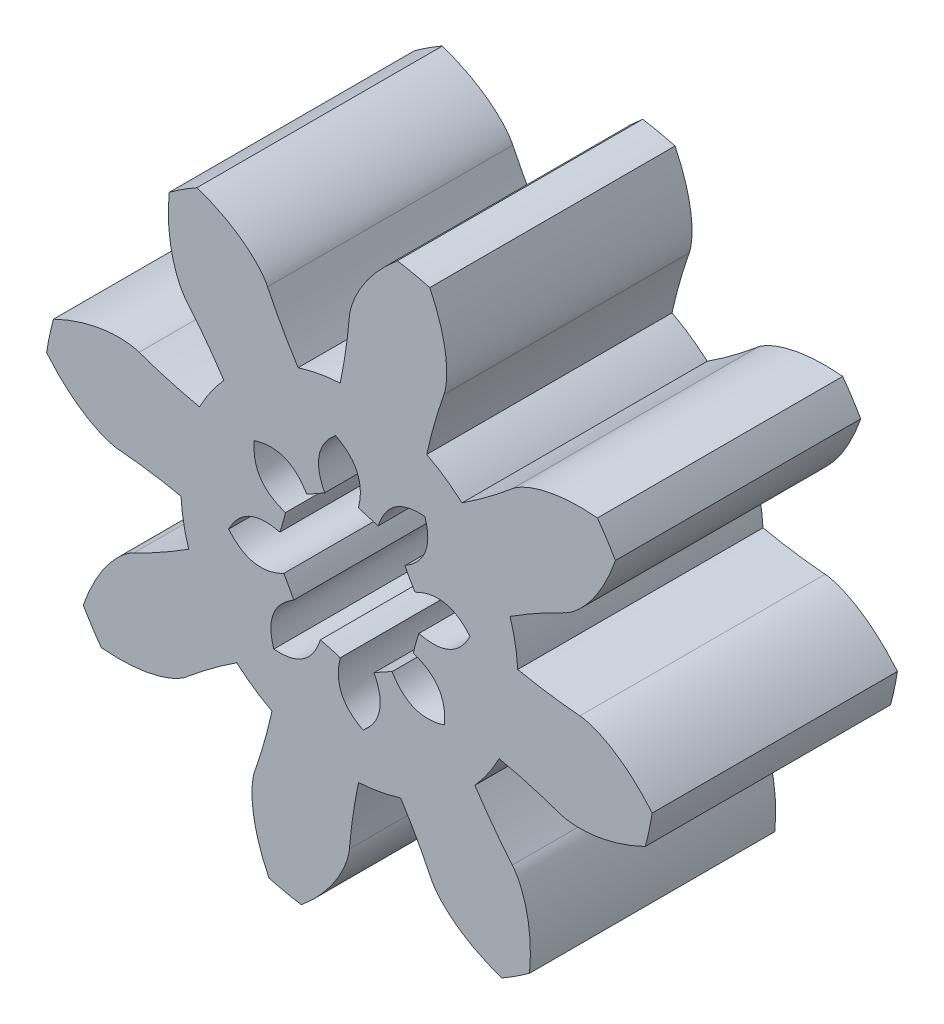
SolidWorks part; units mm, degrees
ref_plane "前视基准面" through (0, 0, 0) normal (0, 0, 1) x (1, 0, 0)
ref_plane "上视基准面" through (0, 0, 0) normal (0, 1, 0) x (1, 0, 0)
ref_plane "右视基准面" through (0, 0, 0) normal (1, 0, 0) x (0, 0, -1)
sketch "草图2" plane through (0, 0, 0) normal (0, 0, 1) x (1, 0, 0)
  line L0 (1021.8666, 5609.6844) -> (5289.866, 5609.6844) construction
  line L1 (0, 0) -> (-0.3395, 2.9526) construction
  line L2 (0, 0) -> (0.0894, 5.9993) construction
  line L3 (0, 0) -> (1.9737, 9.2034) construction
  line L4 (0, 0) -> (6.3967, 9.2712) construction
  circle A0 centre (0, 0) radius 1 construction
  circle A1 centre (0, 0) radius 4.125
  circle A2 centre (0, 0) radius 7.5
  circle A3 centre (0, 0) radius 6
  spline S0 degree 2 poles (-0.6033, 1.6046) (-1.0063, 2.3892) (-0.3395, 2.9526) knots 0 0 0 1 1 1
  spline S1 degree 2 poles (0.2233, 1.6996) (0.4378, 2.5552) (-0.3395, 2.9526) knots 0 0 0 1 1 1
  spline S2 degree 2 poles (0.708, 1.5612) (0.9778, 2.401) (1.8478, 2.3279) knots 0 0 0 1 1 1
  spline S3 degree 2 poles (1.3597, 1.0439) (2.1164, 1.4973) (1.8478, 2.3279) knots 0 0 0 1 1 1
  spline S4 degree 2 poles (1.6046, 0.6033) (2.3892, 1.0063) (2.9526, 0.3395) knots 0 0 0 1 1 1
  spline S5 degree 2 poles (1.6996, -0.2233) (2.5552, -0.4378) (2.9526, 0.3395) knots 0 0 0 1 1 1
  spline S6 degree 2 poles (1.5612, -0.708) (2.401, -0.9778) (2.3279, -1.8478) knots 0 0 0 1 1 1
  spline S7 degree 2 poles (1.0439, -1.3597) (1.4973, -2.1164) (2.3279, -1.8478) knots 0 0 0 1 1 1
  spline S8 degree 2 poles (0.6033, -1.6046) (1.0063, -2.3892) (0.3395, -2.9526) knots 0 0 0 1 1 1
  spline S9 degree 2 poles (-0.2233, -1.6996) (-0.4378, -2.5552) (0.3395, -2.9526) knots 0 0 0 1 1 1
  spline S10 degree 2 poles (-0.708, -1.5612) (-0.9778, -2.401) (-1.8478, -2.3279) knots 0 0 0 1 1 1
  spline S11 degree 2 poles (-1.3597, -1.0439) (-2.1164, -1.4973) (-1.8478, -2.3279) knots 0 0 0 1 1 1
  spline S12 degree 2 poles (-1.6046, -0.6033) (-2.3892, -1.0063) (-2.9526, -0.3395) knots 0 0 0 1 1 1
  spline S13 degree 2 poles (-1.6996, 0.2233) (-2.5552, 0.4378) (-2.9526, -0.3395) knots 0 0 0 1 1 1
  spline S14 degree 2 poles (-1.5612, 0.708) (-2.401, 0.9778) (-2.3279, 1.8478) knots 0 0 0 1 1 1
  spline S15 degree 2 poles (-1.0439, 1.3597) (-1.4973, 2.1164) (-2.3279, 1.8478) knots 0 0 0 1 1 1
  spline S16 degree 2 poles (-1.0439, 1.3597) (-0.8193, 1.4745) (-0.6033, 1.6046) knots 0 0 0 1 1 1
  spline S17 degree 2 poles (0.2233, 1.6996) (0.4633, 1.622) (0.708, 1.5612) knots 0 0 0 1 1 1
  spline S18 degree 2 poles (1.3597, 1.0439) (1.4745, 0.8193) (1.6046, 0.6033) knots 0 0 0 1 1 1
  spline S19 degree 2 poles (1.6996, -0.2233) (1.622, -0.4633) (1.5612, -0.708) knots 0 0 0 1 1 1
  spline S20 degree 2 poles (1.0439, -1.3597) (0.8193, -1.4745) (0.6033, -1.6046) knots 0 0 0 1 1 1
  spline S21 degree 2 poles (-0.2233, -1.6996) (-0.4633, -1.622) (-0.708, -1.5612) knots 0 0 0 1 1 1
  spline S22 degree 2 poles (-1.3597, -1.0439) (-1.4745, -0.8193) (-1.6046, -0.6033) knots 0 0 0 1 1 1
  spline S23 degree 2 poles (-1.6996, 0.2233) (-1.622, 0.4633) (-1.5612, 0.708) knots 0 0 0 1 1 1
  spline S24 degree 4 poles (0, 5.6382) (0.0001, 5.6427) (0.0007, 5.6555) (0.0031, 5.6797) (0.0087, 5.7189) (0.0184, 5.7686) (0.0339, 5.8322) (0.0558, 5.9064) (0.0838, 5.9869) (0.1183, 6.0733) (0.1564, 6.1582) (0.1977, 6.2417) (0.2417, 6.3236) (0.2985, 6.4213) (0.3712, 6.5363) (0.463, 6.6672) (0.5748, 6.8112) (0.6967, 6.9529) (0.8232, 7.0879) (0.9581, 7.219) (1.0936, 7.3421) (1.2411, 7.4639) (1.3809, 7.5734) (1.5445, 7.6892) (1.6787, 7.7806) (1.8629, 7.8935) (1.9738, 7.9579) (2.1059, 8.0304) (2.1658, 8.0612) (2.2027, 8.0802) knots 0 0 0 0 0 0.005377 0.015084 0.028532 0.04661 0.064855 0.092111 0.119476 0.146842 0.174209 0.201575 0.228941 0.256307 0.307035 0.361767 0.4165 0.471232 0.525964 0.580697 0.635429 0.690161 0.744894 0.799626 0.854358 0.909091 0.954545 1 1 1 1 1 construction
  spline S25 degree 4 poles (0, 5.6382) (0.0001, 5.6427) (0.0007, 5.6555) (0.0031, 5.6797) (0.0087, 5.7189) (0.0184, 5.7686) (0.0339, 5.8322) (0.0558, 5.9064) (0.0838, 5.9869) (0.1183, 6.0733) (0.1564, 6.1582) (0.1977, 6.2417) (0.2417, 6.3236) (0.2985, 6.4213) (0.3712, 6.5363) (0.463, 6.6672) (0.5748, 6.8112) (0.6967, 6.9529) (0.8232, 7.0879) (0.9581, 7.219) (1.0611, 7.3126) (1.1345, 7.3751) (1.1722, 7.4063) (1.1737, 7.4076) knots 0 0 0 0 0 0.005377 0.015084 0.028532 0.04661 0.064855 0.092111 0.119476 0.146842 0.174209 0.201575 0.228941 0.256307 0.307035 0.361767 0.4165 0.471232 0.525964 0.580697 0.635429 0.637784 0.637784 0.637784 0.637784 0.637784
  spline S26 degree 2 poles (0, 5.6382) (-0.0656, 4.8718) (-0.2233, 4.119) knots 0 0 0 1 1 1
  spline S27 degree 2 poles (2.3119, 5.1424) (2.0575, 4.4165) (1.8926, 3.6652) knots 0 0 0 1 1 1
  spline S28 degree 4 poles (2.3119, 5.1424) (2.3137, 5.1466) (2.3184, 5.1585) (2.3262, 5.1815) (2.3371, 5.2196) (2.3486, 5.2689) (2.3606, 5.3332) (2.371, 5.4099) (2.3785, 5.4948) (2.3824, 5.5877) (2.3825, 5.6808) (2.3791, 5.7738) (2.3725, 5.8667) (2.3608, 5.9791) (2.3416, 6.1138) (2.3116, 6.2707) (2.2687, 6.4479) (2.2155, 6.6271) (2.1556, 6.8022) (2.0863, 6.9771) (2.0307, 7.1047) (1.9894, 7.1917) (1.9678, 7.2357) (1.967, 7.2375) knots 0 0 0 0 0 0.005377 0.015084 0.028532 0.04661 0.064855 0.092111 0.119476 0.146842 0.174209 0.201575 0.228941 0.256307 0.307035 0.361767 0.4165 0.471232 0.525964 0.580697 0.635429 0.637784 0.637784 0.637784 0.637784 0.637784
  spline S29 degree 2 poles (3.9868, 3.9868) (3.3985, 3.4913) (2.7547, 3.0704) knots 0 0 0 1 1 1
  spline S30 degree 4 poles (3.9868, 3.9868) (3.9901, 3.9899) (3.9996, 3.9986) (4.0183, 4.014) (4.05, 4.0378) (4.092, 4.066) (4.148, 4.1001) (4.2159, 4.137) (4.2926, 4.1741) (4.3781, 4.2108) (4.4651, 4.2439) (4.5533, 4.2738) (4.6424, 4.3006) (4.7516, 4.3295) (4.8844, 4.3594) (5.0418, 4.387) (5.2227, 4.4098) (5.4091, 4.4237) (5.594, 4.4298) (5.7821, 4.4272) (5.9211, 4.4205) (6.0172, 4.4127) (6.0659, 4.4082) (6.0679, 4.408) knots 0 0 0 0 0 0.005377 0.015084 0.028532 0.04661 0.064855 0.092111 0.119476 0.146842 0.174209 0.201575 0.228941 0.256307 0.307035 0.361767 0.4165 0.471232 0.525964 0.580697 0.635429 0.637784 0.637784 0.637784 0.637784 0.637784
  point P48 (0, 0)
  point P70 (0, 0)
  dimension "D1" = 2
  dimension "D2" = 15
  dimension "D3" = 8.25
  dimension "D4" = 12
  dimension "D5" = 11.25
  dimension "D6" = 33.75
sketch "草图3" plane through (0, 0, 0) normal (0, 0, 1) x (1, 0, 0)
  circle A0 centre (0, 0) radius 7.5 construction
  circle A1 centre (0, 0) radius 4.125 construction
  arc A3 (2.3119, 5.1424) -> (1.8926, 3.6652) centre (14.2794, 0.9473) ccw construction
  arc A4 (-0.2233, 4.119) -> (0, 5.6382) centre (-12.6353, 6.7192) ccw construction
  arc A5 (1.967, 7.2375) -> (1.1737, 7.4076) centre (0, 0) ccw
  arc A6 (2.7547, 3.0704) -> (1.8926, 3.6652) centre (0, 0) ccw
  arc A8 (2.3119, 5.1424) -> (1.8926, 3.6652) centre (14.2794, 0.9473) ccw
  arc A9 (-0.2233, 4.119) -> (0, 5.6382) centre (-12.6353, 6.7192) ccw
  arc A10 (2.7547, 3.0704) -> (3.9868, 3.9868) centre (-4.1833, 13.6857) ccw
  arc A11 (6.5085, 3.7268) -> (6.0679, 4.408) centre (0, 0) ccw
  arc A12 (5.271, 2.0014) -> (3.93, 1.2534) centre (10.7669, -9.4272) ccw
  arc A13 (4.119, 0.2233) -> (3.93, 1.2534) centre (0, 0) ccw
  arc A14 (4.119, 0.2233) -> (5.6382, 0) centre (6.7192, 12.6353) ccw
  arc A15 (7.2375, -1.967) -> (7.4076, -1.1737) centre (0, 0) ccw
  arc A16 (5.1424, -2.3119) -> (3.6652, -1.8926) centre (0.9473, -14.2794) ccw
  arc A17 (3.0704, -2.7547) -> (3.6652, -1.8926) centre (0, 0) ccw
  arc A18 (3.0704, -2.7547) -> (3.9868, -3.9868) centre (13.6857, 4.1833) ccw
  arc A19 (3.7268, -6.5085) -> (4.408, -6.0679) centre (0, 0) ccw
  arc A20 (2.0014, -5.271) -> (1.2534, -3.93) centre (-9.4272, -10.7669) ccw
  arc A21 (0.2233, -4.119) -> (1.2534, -3.93) centre (0, 0) ccw
  arc A22 (0.2233, -4.119) -> (0, -5.6382) centre (12.6353, -6.7192) ccw
  arc A23 (-1.967, -7.2375) -> (-1.1737, -7.4076) centre (0, 0) ccw
  arc A24 (-2.3119, -5.1424) -> (-1.8926, -3.6652) centre (-14.2794, -0.9473) ccw
  arc A25 (-2.7547, -3.0704) -> (-1.8926, -3.6652) centre (0, 0) ccw
  arc A26 (-2.7547, -3.0704) -> (-3.9868, -3.9868) centre (4.1833, -13.6857) ccw
  arc A27 (-6.5085, -3.7268) -> (-6.0679, -4.408) centre (0, 0) ccw
  arc A28 (-5.271, -2.0014) -> (-3.93, -1.2534) centre (-10.7669, 9.4272) ccw
  arc A29 (-4.119, -0.2233) -> (-3.93, -1.2534) centre (0, 0) ccw
  arc A30 (-4.119, -0.2233) -> (-5.6382, 0) centre (-6.7192, -12.6353) ccw
  arc A31 (-7.2375, 1.967) -> (-7.4076, 1.1737) centre (0, 0) ccw
  arc A32 (-5.1424, 2.3119) -> (-3.6652, 1.8926) centre (-0.9473, 14.2794) ccw
  arc A33 (-3.0704, 2.7547) -> (-3.6652, 1.8926) centre (0, 0) ccw
  arc A34 (-3.0704, 2.7547) -> (-3.9868, 3.9868) centre (-13.6857, -4.1833) ccw
  arc A35 (-3.7268, 6.5085) -> (-4.408, 6.0679) centre (0, 0) ccw
  arc A36 (-2.0014, 5.271) -> (-1.2534, 3.93) centre (9.4272, 10.7669) ccw
  arc A37 (-0.2233, 4.119) -> (-1.2534, 3.93) centre (0, 0) ccw
  spline S1 degree 4 poles (-1827.5886, 812.2338) (-20.5673, 13.6102) (1.554, 4.3385) (2.187, 4.6983) (2.3371, 5.2196) (2.3486, 5.2689) (2.3606, 5.3332) (2.371, 5.4099) (2.3785, 5.4948) (2.3824, 5.5877) (2.3825, 5.6808) (2.3791, 5.7738) (2.3725, 5.8667) (2.3608, 5.9791) (2.3416, 6.1138) (2.3116, 6.2707) (2.2687, 6.4479) (2.2155, 6.6271) (2.1556, 6.8022) (2.0863, 6.9771) (1.4771, 8.3746) (-0.1138, 10.0692) (14.7711, -11.5034) (-1169.1431, 1628.4646) knots -0.591364 -0.591364 -0.591364 -0.591364 -0.591364 0.005377 0.015084 0.028532 0.04661 0.064855 0.092111 0.119476 0.146842 0.174209 0.201575 0.228941 0.256307 0.307035 0.361767 0.4165 0.471232 0.525964 0.580697 0.635429 2.294974 2.294974 2.294974 2.294974 2.294974 only from (2.3119, 5.1424) to (1.967, 7.2375) construction
  spline S2 degree 4 poles (1999.9325, -8.5916) (24.3395, 3.9798) (0.3616, 4.5942) (-0.0681, 5.1819) (0.0087, 5.7189) (0.0184, 5.7686) (0.0339, 5.8322) (0.0558, 5.9064) (0.0838, 5.9869) (0.1183, 6.0733) (0.1564, 6.1582) (0.1977, 6.2417) (0.2417, 6.3236) (0.2985, 6.4213) (0.3712, 6.5363) (0.463, 6.6672) (0.5748, 6.8112) (0.6967, 6.9529) (0.8232, 7.0879) (0.9581, 7.219) (2.0868, 8.2439) (4.2327, 9.1371) (-18.1891, -4.435) (1734.0829, 1005.8577) knots -0.591364 -0.591364 -0.591364 -0.591364 -0.591364 0.005377 0.015084 0.028532 0.04661 0.064855 0.092111 0.119476 0.146842 0.174209 0.201575 0.228941 0.256307 0.307035 0.361767 0.4165 0.471232 0.525964 0.580697 0.635429 2.294974 2.294974 2.294974 2.294974 2.294974 only from (0, 5.6382) to (1.1737, 7.4076) construction
  spline S3 degree 4 poles (3.9868, 3.9868) (3.9901, 3.9899) (3.9996, 3.9986) (4.0183, 4.014) (4.05, 4.0378) (4.092, 4.066) (4.148, 4.1001) (4.2159, 4.137) (4.2926, 4.1741) (4.3781, 4.2108) (4.4651, 4.2439) (4.5533, 4.2738) (4.6424, 4.3006) (4.7516, 4.3295) (4.8844, 4.3594) (5.0418, 4.387) (5.2227, 4.4098) (5.4091, 4.4237) (5.594, 4.4298) (5.7821, 4.4272) (5.9211, 4.4205) (6.0172, 4.4127) (6.0659, 4.4082) (6.0679, 4.408) knots 0 0 0 0 0 0.005377 0.015084 0.028532 0.04661 0.064855 0.092111 0.119476 0.146842 0.174209 0.201575 0.228941 0.256307 0.307035 0.361767 0.4165 0.471232 0.525964 0.580697 0.635429 0.637784 0.637784 0.637784 0.637784 0.637784
  spline S4 degree 4 poles (2.3119, 5.1424) (2.3137, 5.1466) (2.3184, 5.1585) (2.3262, 5.1815) (2.3371, 5.2196) (2.3486, 5.2689) (2.3606, 5.3332) (2.371, 5.4099) (2.3785, 5.4948) (2.3824, 5.5877) (2.3825, 5.6808) (2.3791, 5.7738) (2.3725, 5.8667) (2.3608, 5.9791) (2.3416, 6.1138) (2.3116, 6.2707) (2.2687, 6.4479) (2.2155, 6.6271) (2.1556, 6.8022) (2.0863, 6.9771) (2.0307, 7.1047) (1.9894, 7.1917) (1.9678, 7.2357) (1.967, 7.2375) knots 0 0 0 0 0 0.005377 0.015084 0.028532 0.04661 0.064855 0.092111 0.119476 0.146842 0.174209 0.201575 0.228941 0.256307 0.307035 0.361767 0.4165 0.471232 0.525964 0.580697 0.635429 0.637784 0.637784 0.637784 0.637784 0.637784
  spline S5 degree 4 poles (0, 5.6382) (0.0001, 5.6427) (0.0007, 5.6555) (0.0031, 5.6797) (0.0087, 5.7189) (0.0184, 5.7686) (0.0339, 5.8322) (0.0558, 5.9064) (0.0838, 5.9869) (0.1183, 6.0733) (0.1564, 6.1582) (0.1977, 6.2417) (0.2417, 6.3236) (0.2985, 6.4213) (0.3712, 6.5363) (0.463, 6.6672) (0.5748, 6.8112) (0.6967, 6.9529) (0.8232, 7.0879) (0.9581, 7.219) (1.0611, 7.3126) (1.1345, 7.3751) (1.1722, 7.4063) (1.1737, 7.4076) knots 0 0 0 0 0 0.005377 0.015084 0.028532 0.04661 0.064855 0.092111 0.119476 0.146842 0.174209 0.201575 0.228941 0.256307 0.307035 0.361767 0.4165 0.471232 0.525964 0.580697 0.635429 0.637784 0.637784 0.637784 0.637784 0.637784
  spline S6 degree 4 poles (5.271, 2.0014) (5.2752, 2.0031) (5.287, 2.0082) (5.3087, 2.019) (5.3434, 2.0382) (5.3864, 2.0649) (5.4404, 2.102) (5.5019, 2.1488) (5.5673, 2.2036) (5.6357, 2.2665) (5.7016, 2.3322) (5.765, 2.4004) (5.826, 2.4707) (5.8972, 2.5585) (5.9789, 2.6673) (6.0686, 2.7995) (6.1636, 2.9552) (6.2527, 3.1195) (6.3341, 3.2856) (6.4088, 3.4583) (6.4597, 3.5879) (6.492, 3.6786) (6.5079, 3.7249) (6.5085, 3.7268) knots 0 0 0 0 0 0.005377 0.015084 0.028532 0.04661 0.064855 0.092111 0.119476 0.146842 0.174209 0.201575 0.228941 0.256307 0.307035 0.361767 0.4165 0.471232 0.525964 0.580697 0.635429 0.637784 0.637784 0.637784 0.637784 0.637784
  spline S7 degree 4 poles (5.6382, 0) (5.6427, -0.0001) (5.6555, -0.0007) (5.6797, -0.0031) (5.7189, -0.0087) (5.7686, -0.0184) (5.8322, -0.0339) (5.9064, -0.0558) (5.9869, -0.0838) (6.0733, -0.1183) (6.1582, -0.1564) (6.2417, -0.1977) (6.3236, -0.2417) (6.4213, -0.2985) (6.5363, -0.3712) (6.6672, -0.463) (6.8112, -0.5748) (6.9529, -0.6967) (7.0879, -0.8232) (7.219, -0.9581) (7.3126, -1.0611) (7.3751, -1.1345) (7.4063, -1.1722) (7.4076, -1.1737) knots 0 0 0 0 0 0.005377 0.015084 0.028532 0.04661 0.064855 0.092111 0.119476 0.146842 0.174209 0.201575 0.228941 0.256307 0.307035 0.361767 0.4165 0.471232 0.525964 0.580697 0.635429 0.637784 0.637784 0.637784 0.637784 0.637784
  spline S8 degree 4 poles (5.1424, -2.3119) (5.1466, -2.3137) (5.1585, -2.3184) (5.1815, -2.3262) (5.2196, -2.3371) (5.2689, -2.3486) (5.3332, -2.3606) (5.4099, -2.371) (5.4948, -2.3785) (5.5877, -2.3824) (5.6808, -2.3825) (5.7738, -2.3791) (5.8667, -2.3725) (5.9791, -2.3608) (6.1138, -2.3416) (6.2707, -2.3116) (6.4479, -2.2687) (6.6271, -2.2155) (6.8022, -2.1556) (6.9771, -2.0863) (7.1047, -2.0307) (7.1917, -1.9894) (7.2357, -1.9678) (7.2375, -1.967) knots 0 0 0 0 0 0.005377 0.015084 0.028532 0.04661 0.064855 0.092111 0.119476 0.146842 0.174209 0.201575 0.228941 0.256307 0.307035 0.361767 0.4165 0.471232 0.525964 0.580697 0.635429 0.637784 0.637784 0.637784 0.637784 0.637784
  spline S9 degree 4 poles (3.9868, -3.9868) (3.9899, -3.9901) (3.9986, -3.9996) (4.014, -4.0183) (4.0378, -4.05) (4.066, -4.092) (4.1001, -4.148) (4.137, -4.2159) (4.1741, -4.2926) (4.2108, -4.3781) (4.2439, -4.4651) (4.2738, -4.5533) (4.3006, -4.6424) (4.3295, -4.7516) (4.3594, -4.8844) (4.387, -5.0418) (4.4098, -5.2227) (4.4237, -5.4091) (4.4298, -5.594) (4.4272, -5.7821) (4.4205, -5.9211) (4.4127, -6.0172) (4.4082, -6.0659) (4.408, -6.0679) knots 0 0 0 0 0 0.005377 0.015084 0.028532 0.04661 0.064855 0.092111 0.119476 0.146842 0.174209 0.201575 0.228941 0.256307 0.307035 0.361767 0.4165 0.471232 0.525964 0.580697 0.635429 0.637784 0.637784 0.637784 0.637784 0.637784
  spline S10 degree 4 poles (2.0014, -5.271) (2.0031, -5.2752) (2.0082, -5.287) (2.019, -5.3087) (2.0382, -5.3434) (2.0649, -5.3864) (2.102, -5.4404) (2.1488, -5.5019) (2.2036, -5.5673) (2.2665, -5.6357) (2.3322, -5.7016) (2.4004, -5.765) (2.4707, -5.826) (2.5585, -5.8972) (2.6673, -5.9789) (2.7995, -6.0686) (2.9552, -6.1636) (3.1195, -6.2527) (3.2856, -6.3341) (3.4583, -6.4088) (3.5879, -6.4597) (3.6786, -6.492) (3.7249, -6.5079) (3.7268, -6.5085) knots 0 0 0 0 0 0.005377 0.015084 0.028532 0.04661 0.064855 0.092111 0.119476 0.146842 0.174209 0.201575 0.228941 0.256307 0.307035 0.361767 0.4165 0.471232 0.525964 0.580697 0.635429 0.637784 0.637784 0.637784 0.637784 0.637784
  spline S11 degree 4 poles (0, -5.6382) (-0.0001, -5.6427) (-0.0007, -5.6555) (-0.0031, -5.6797) (-0.0087, -5.7189) (-0.0184, -5.7686) (-0.0339, -5.8322) (-0.0558, -5.9064) (-0.0838, -5.9869) (-0.1183, -6.0733) (-0.1564, -6.1582) (-0.1977, -6.2417) (-0.2417, -6.3236) (-0.2985, -6.4213) (-0.3712, -6.5363) (-0.463, -6.6672) (-0.5748, -6.8112) (-0.6967, -6.9529) (-0.8232, -7.0879) (-0.9581, -7.219) (-1.0611, -7.3126) (-1.1345, -7.3751) (-1.1722, -7.4063) (-1.1737, -7.4076) knots 0 0 0 0 0 0.005377 0.015084 0.028532 0.04661 0.064855 0.092111 0.119476 0.146842 0.174209 0.201575 0.228941 0.256307 0.307035 0.361767 0.4165 0.471232 0.525964 0.580697 0.635429 0.637784 0.637784 0.637784 0.637784 0.637784
  spline S12 degree 4 poles (-2.3119, -5.1424) (-2.3137, -5.1466) (-2.3184, -5.1585) (-2.3262, -5.1815) (-2.3371, -5.2196) (-2.3486, -5.2689) (-2.3606, -5.3332) (-2.371, -5.4099) (-2.3785, -5.4948) (-2.3824, -5.5877) (-2.3825, -5.6808) (-2.3791, -5.7738) (-2.3725, -5.8667) (-2.3608, -5.9791) (-2.3416, -6.1138) (-2.3116, -6.2707) (-2.2687, -6.4479) (-2.2155, -6.6271) (-2.1556, -6.8022) (-2.0863, -6.9771) (-2.0307, -7.1047) (-1.9894, -7.1917) (-1.9678, -7.2357) (-1.967, -7.2375) knots 0 0 0 0 0 0.005377 0.015084 0.028532 0.04661 0.064855 0.092111 0.119476 0.146842 0.174209 0.201575 0.228941 0.256307 0.307035 0.361767 0.4165 0.471232 0.525964 0.580697 0.635429 0.637784 0.637784 0.637784 0.637784 0.637784
  spline S13 degree 4 poles (-3.9868, -3.9868) (-3.9901, -3.9899) (-3.9996, -3.9986) (-4.0183, -4.014) (-4.05, -4.0378) (-4.092, -4.066) (-4.148, -4.1001) (-4.2159, -4.137) (-4.2926, -4.1741) (-4.3781, -4.2108) (-4.4651, -4.2439) (-4.5533, -4.2738) (-4.6424, -4.3006) (-4.7516, -4.3295) (-4.8844, -4.3594) (-5.0418, -4.387) (-5.2227, -4.4098) (-5.4091, -4.4237) (-5.594, -4.4298) (-5.7821, -4.4272) (-5.9211, -4.4205) (-6.0172, -4.4127) (-6.0659, -4.4082) (-6.0679, -4.408) knots 0 0 0 0 0 0.005377 0.015084 0.028532 0.04661 0.064855 0.092111 0.119476 0.146842 0.174209 0.201575 0.228941 0.256307 0.307035 0.361767 0.4165 0.471232 0.525964 0.580697 0.635429 0.637784 0.637784 0.637784 0.637784 0.637784
  spline S14 degree 4 poles (-5.271, -2.0014) (-5.2752, -2.0031) (-5.287, -2.0082) (-5.3087, -2.019) (-5.3434, -2.0382) (-5.3864, -2.0649) (-5.4404, -2.102) (-5.5019, -2.1488) (-5.5673, -2.2036) (-5.6357, -2.2665) (-5.7016, -2.3322) (-5.765, -2.4004) (-5.826, -2.4707) (-5.8972, -2.5585) (-5.9789, -2.6673) (-6.0686, -2.7995) (-6.1636, -2.9552) (-6.2527, -3.1195) (-6.3341, -3.2856) (-6.4088, -3.4583) (-6.4597, -3.5879) (-6.492, -3.6786) (-6.5079, -3.7249) (-6.5085, -3.7268) knots 0 0 0 0 0 0.005377 0.015084 0.028532 0.04661 0.064855 0.092111 0.119476 0.146842 0.174209 0.201575 0.228941 0.256307 0.307035 0.361767 0.4165 0.471232 0.525964 0.580697 0.635429 0.637784 0.637784 0.637784 0.637784 0.637784
  spline S15 degree 4 poles (-5.6382, 0) (-5.6427, 0.0001) (-5.6555, 0.0007) (-5.6797, 0.0031) (-5.7189, 0.0087) (-5.7686, 0.0184) (-5.8322, 0.0339) (-5.9064, 0.0558) (-5.9869, 0.0838) (-6.0733, 0.1183) (-6.1582, 0.1564) (-6.2417, 0.1977) (-6.3236, 0.2417) (-6.4213, 0.2985) (-6.5363, 0.3712) (-6.6672, 0.463) (-6.8112, 0.5748) (-6.9529, 0.6967) (-7.0879, 0.8232) (-7.219, 0.9581) (-7.3126, 1.0611) (-7.3751, 1.1345) (-7.4063, 1.1722) (-7.4076, 1.1737) knots 0 0 0 0 0 0.005377 0.015084 0.028532 0.04661 0.064855 0.092111 0.119476 0.146842 0.174209 0.201575 0.228941 0.256307 0.307035 0.361767 0.4165 0.471232 0.525964 0.580697 0.635429 0.637784 0.637784 0.637784 0.637784 0.637784
  spline S16 degree 4 poles (-5.1424, 2.3119) (-5.1466, 2.3137) (-5.1585, 2.3184) (-5.1815, 2.3262) (-5.2196, 2.3371) (-5.2689, 2.3486) (-5.3332, 2.3606) (-5.4099, 2.371) (-5.4948, 2.3785) (-5.5877, 2.3824) (-5.6808, 2.3825) (-5.7738, 2.3791) (-5.8667, 2.3725) (-5.9791, 2.3608) (-6.1138, 2.3416) (-6.2707, 2.3116) (-6.4479, 2.2687) (-6.6271, 2.2155) (-6.8022, 2.1556) (-6.9771, 2.0863) (-7.1047, 2.0307) (-7.1917, 1.9894) (-7.2357, 1.9678) (-7.2375, 1.967) knots 0 0 0 0 0 0.005377 0.015084 0.028532 0.04661 0.064855 0.092111 0.119476 0.146842 0.174209 0.201575 0.228941 0.256307 0.307035 0.361767 0.4165 0.471232 0.525964 0.580697 0.635429 0.637784 0.637784 0.637784 0.637784 0.637784
  spline S17 degree 4 poles (-3.9868, 3.9868) (-3.9899, 3.9901) (-3.9986, 3.9996) (-4.014, 4.0183) (-4.0378, 4.05) (-4.066, 4.092) (-4.1001, 4.148) (-4.137, 4.2159) (-4.1741, 4.2926) (-4.2108, 4.3781) (-4.2439, 4.4651) (-4.2738, 4.5533) (-4.3006, 4.6424) (-4.3295, 4.7516) (-4.3594, 4.8844) (-4.387, 5.0418) (-4.4098, 5.2227) (-4.4237, 5.4091) (-4.4298, 5.594) (-4.4272, 5.7821) (-4.4205, 5.9211) (-4.4127, 6.0172) (-4.4082, 6.0659) (-4.408, 6.0679) knots 0 0 0 0 0 0.005377 0.015084 0.028532 0.04661 0.064855 0.092111 0.119476 0.146842 0.174209 0.201575 0.228941 0.256307 0.307035 0.361767 0.4165 0.471232 0.525964 0.580697 0.635429 0.637784 0.637784 0.637784 0.637784 0.637784
  spline S18 degree 4 poles (-2.0014, 5.271) (-2.0031, 5.2752) (-2.0082, 5.287) (-2.019, 5.3087) (-2.0382, 5.3434) (-2.0649, 5.3864) (-2.102, 5.4404) (-2.1488, 5.5019) (-2.2036, 5.5673) (-2.2665, 5.6357) (-2.3322, 5.7016) (-2.4004, 5.765) (-2.4707, 5.826) (-2.5585, 5.8972) (-2.6673, 5.9789) (-2.7995, 6.0686) (-2.9552, 6.1636) (-3.1195, 6.2527) (-3.2856, 6.3341) (-3.4583, 6.4088) (-3.5879, 6.4597) (-3.6786, 6.492) (-3.7249, 6.5079) (-3.7268, 6.5085) knots 0 0 0 0 0 0.005377 0.015084 0.028532 0.04661 0.064855 0.092111 0.119476 0.146842 0.174209 0.201575 0.228941 0.256307 0.307035 0.361767 0.4165 0.471232 0.525964 0.580697 0.635429 0.637784 0.637784 0.637784 0.637784 0.637784
  point P79 (0, 0)
  dimension "D1" = 8
extrude "凸台-拉伸1" add sketch "草图3" along normal blind 6
sketch "草图4" plane through (0, 0, 6) normal (0, 0, 1) x (1, 0, 0)
  arc A0 (-1.0439, 1.3597) -> (-0.6033, 1.6046) centre (-4.3485, 7.8258) ccw construction
  arc A1 (0.2233, 1.6996) -> (0.708, 1.5612) centre (2.4588, 8.6085) ccw construction
  arc A2 (1.3597, 1.0439) -> (1.6046, 0.6033) centre (7.8258, 4.3485) ccw construction
  arc A3 (1.6996, -0.2233) -> (1.5612, -0.708) centre (8.6085, -2.4588) ccw construction
  arc A4 (1.0439, -1.3597) -> (0.6033, -1.6046) centre (4.3485, -7.8258) ccw construction
  arc A5 (-0.2233, -1.6996) -> (-0.708, -1.5612) centre (-2.4588, -8.6085) ccw construction
  arc A6 (-1.3597, -1.0439) -> (-1.6046, -0.6033) centre (-7.8258, -4.3485) ccw construction
  arc A7 (-1.6996, 0.2233) -> (-1.5612, 0.708) centre (-8.6085, 2.4588) ccw construction
  arc A8 (-1.0439, 1.3597) -> (-0.6033, 1.6046) centre (-4.3485, 7.8258) ccw
  arc A9 (0.2233, 1.6996) -> (0.708, 1.5612) centre (2.4588, 8.6085) ccw
  arc A10 (1.3597, 1.0439) -> (1.6046, 0.6033) centre (7.8258, 4.3485) ccw
  arc A11 (1.6996, -0.2233) -> (1.5612, -0.708) centre (8.6085, -2.4588) ccw
  arc A12 (1.0439, -1.3597) -> (0.6033, -1.6046) centre (4.3485, -7.8258) ccw
  arc A13 (-0.2233, -1.6996) -> (-0.708, -1.5612) centre (-2.4588, -8.6085) ccw
  arc A14 (-1.3597, -1.0439) -> (-1.6046, -0.6033) centre (-7.8258, -4.3485) ccw
  arc A15 (-1.6996, 0.2233) -> (-1.5612, 0.708) centre (-8.6085, 2.4588) ccw
  parabola Q0 (-0.6033, 1.6046) -> (-0.3395, 2.9526) focus (-0.3142, 2.2555) apex (-0.737, 2.3429) construction
  parabola Q1 (0.2233, 1.6996) -> (-0.3395, 2.9526) focus (-0.2059, 2.268) apex (0.186, 2.449) construction
  parabola Q2 (0.708, 1.5612) -> (1.8478, 2.3279) focus (1.3727, 1.8171) apex (1.1355, 2.1778) construction
  parabola Q3 (1.3597, 1.0439) -> (1.8478, 2.3279) focus (1.4581, 1.7493) apex (1.8633, 1.6002) construction
  parabola Q4 (1.6046, 0.6033) -> (2.9526, 0.3395) focus (2.2555, 0.3142) apex (2.3429, 0.737) construction
  parabola Q5 (1.6996, -0.2233) -> (2.9526, 0.3395) focus (2.268, 0.2059) apex (2.449, -0.186) construction
  parabola Q6 (1.5612, -0.708) -> (2.3279, -1.8478) focus (1.8171, -1.3727) apex (2.1778, -1.1355) construction
  parabola Q7 (1.0439, -1.3597) -> (2.3279, -1.8478) focus (1.7493, -1.4581) apex (1.6002, -1.8633) construction
  parabola Q8 (0.6033, -1.6046) -> (0.3395, -2.9526) focus (0.3142, -2.2555) apex (0.737, -2.3429) construction
  parabola Q9 (-0.2233, -1.6996) -> (0.3395, -2.9526) focus (0.2059, -2.268) apex (-0.186, -2.449) construction
  parabola Q10 (-0.708, -1.5612) -> (-1.8478, -2.3279) focus (-1.3727, -1.8171) apex (-1.1355, -2.1778) construction
  parabola Q11 (-1.3597, -1.0439) -> (-1.8478, -2.3279) focus (-1.4581, -1.7493) apex (-1.8633, -1.6002) construction
  parabola Q12 (-1.6046, -0.6033) -> (-2.9526, -0.3395) focus (-2.2555, -0.3142) apex (-2.3429, -0.737) construction
  parabola Q13 (-1.6996, 0.2233) -> (-2.9526, -0.3395) focus (-2.268, -0.2059) apex (-2.449, 0.186) construction
  parabola Q14 (-1.5612, 0.708) -> (-2.3279, 1.8478) focus (-1.8171, 1.3727) apex (-2.1778, 1.1355) construction
  parabola Q15 (-1.0439, 1.3597) -> (-2.3279, 1.8478) focus (-1.7493, 1.4581) apex (-1.6002, 1.8633) construction
  parabola Q16 (-0.6033, 1.6046) -> (-0.3395, 2.9526) focus (-0.3142, 2.2555) apex (-0.737, 2.3429)
  parabola Q17 (0.2233, 1.6996) -> (-0.3395, 2.9526) focus (-0.2059, 2.268) apex (0.186, 2.449)
  parabola Q18 (0.708, 1.5612) -> (1.8478, 2.3279) focus (1.3727, 1.8171) apex (1.1355, 2.1778)
  parabola Q19 (1.3597, 1.0439) -> (1.8478, 2.3279) focus (1.4581, 1.7493) apex (1.8633, 1.6002)
  parabola Q20 (1.6046, 0.6033) -> (2.9526, 0.3395) focus (2.2555, 0.3142) apex (2.3429, 0.737)
  parabola Q21 (1.6996, -0.2233) -> (2.9526, 0.3395) focus (2.268, 0.2059) apex (2.449, -0.186)
  parabola Q22 (1.5612, -0.708) -> (2.3279, -1.8478) focus (1.8171, -1.3727) apex (2.1778, -1.1355)
  parabola Q23 (1.0439, -1.3597) -> (2.3279, -1.8478) focus (1.7493, -1.4581) apex (1.6002, -1.8633)
  parabola Q24 (0.6033, -1.6046) -> (0.3395, -2.9526) focus (0.3142, -2.2555) apex (0.737, -2.3429)
  parabola Q25 (-0.2233, -1.6996) -> (0.3395, -2.9526) focus (0.2059, -2.268) apex (-0.186, -2.449)
  parabola Q26 (-0.708, -1.5612) -> (-1.8478, -2.3279) focus (-1.3727, -1.8171) apex (-1.1355, -2.1778)
  parabola Q27 (-1.3597, -1.0439) -> (-1.8478, -2.3279) focus (-1.4581, -1.7493) apex (-1.8633, -1.6002)
  parabola Q28 (-1.6046, -0.6033) -> (-2.9526, -0.3395) focus (-2.2555, -0.3142) apex (-2.3429, -0.737)
  parabola Q29 (-1.6996, 0.2233) -> (-2.9526, -0.3395) focus (-2.268, -0.2059) apex (-2.449, 0.186)
  parabola Q30 (-1.5612, 0.708) -> (-2.3279, 1.8478) focus (-1.8171, 1.3727) apex (-2.1778, 1.1355)
  parabola Q31 (-1.0439, 1.3597) -> (-2.3279, 1.8478) focus (-1.7493, 1.4581) apex (-1.6002, 1.8633)
extrude "切除-拉伸2" cut sketch "草图4" against normal through all
